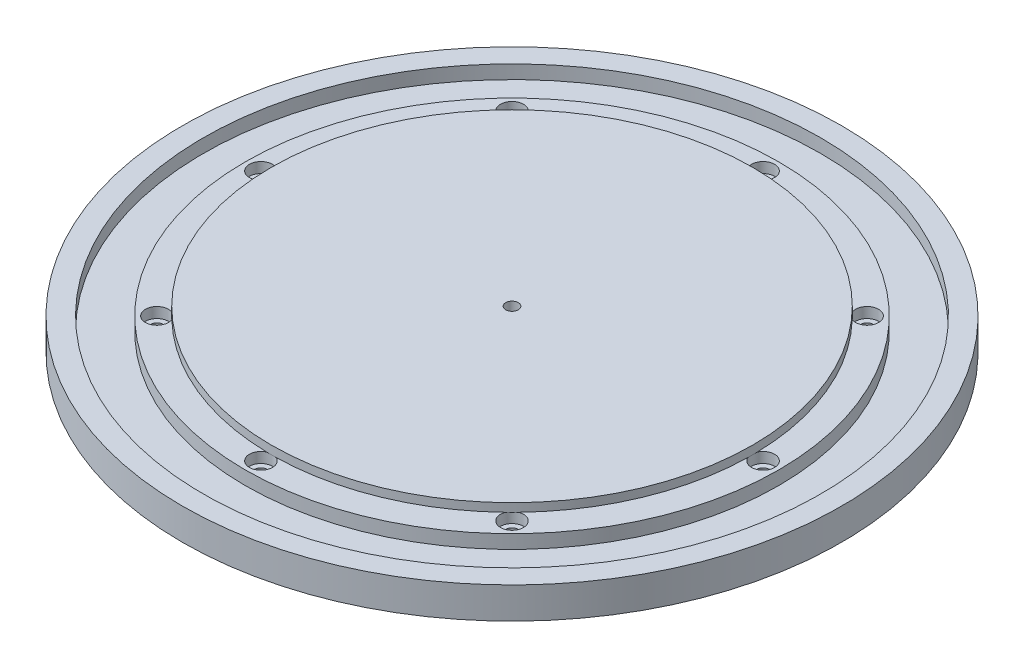
SolidWorks part; units mm, degrees
ref_plane "Front Plane" through (0, 0, 0) normal (0, 0, 1) x (1, 0, 0)
ref_plane "Top Plane" through (0, 0, 0) normal (0, 1, 0) x (1, 0, 0)
ref_plane "Right Plane" through (0, 0, 0) normal (1, 0, 0) x (0, 0, -1)
sketch "Sketch1" plane through (0, 0, 0) normal (1, 0, 0) x (0, 0, -1)
  line L0 (0, -1000) -> (0, 49000) construction
  line L12 (-315, 14.606) -> (-315, 44.606)
  line L13 (-315, 44.606) -> (-295, 44.606)
  line L14 (-295, 44.606) -> (-295, 31.606)
  line L15 (-295, 31.606) -> (-255, 31.606)
  line L16 (-255, 31.606) -> (-255, 44.606)
  line L18 (-255, 44.606) -> (-230, 44.606)
  line L19 (-315, 14.606) -> (-229.5, 14.606)
  line L21 (-229.5, 14.606) -> (0, 14.606)
  line L22 (0, 14.606) -> (0, 44.606)
  line L24 (-230, 44.606) -> (-230, 52.606)
  line L25 (-230, 52.606) -> (0, 52.606)
  line L26 (0, 52.606) -> (0, 44.606)
  dimension "D1" = 30
  dimension "D2" = 13
  dimension "D3" = 8
  dimension "D4" = 630
  dimension "D5" = 460
  dimension "D6" = 40
  dimension "D9" = 20
  dimension "D10" = 510
  dimension "D11" = 13
revolve "Revolve1" add sketch "Sketch1" angle 360 about L0
sketch "Sketch2" plane through (0, 44.606, 0) normal (0, 1, 0) x (1, 0, 0)
  line L0 (0, -1000) -> (0, 49000) construction
  line L1 (-1000, 0) -> (49000, 0) construction
  circle A0 centre (0, 240) radius 11
  circle A1 centre (169.7056, 169.7056) radius 11
  circle A2 centre (240, 0) radius 11
  circle A3 centre (169.7056, -169.7056) radius 11
  circle A4 centre (0, -240) radius 11
  circle A5 centre (-169.7056, -169.7056) radius 11
  circle A6 centre (-240, 0) radius 11
  circle A7 centre (-169.7056, 169.7056) radius 11
  point P23 (0, 0)
  dimension "D1" = 240
  dimension "D2" = 22
  dimension "D3" = 8
extrude "Cut-Extrude1" cut sketch "Sketch2" against normal blind 10
sketch "Sketch3" plane through (0, 44.606, 0) normal (0, 1, 0) x (1, 0, 0)
  line L0 (0, -1000) -> (0, 49000) construction
  line L1 (-1000, 0) -> (49000, 0) construction
  circle A0 centre (0, 240) radius 6
  circle A1 centre (169.7056, 169.7056) radius 6
  circle A2 centre (240, 0) radius 6
  circle A3 centre (169.7056, -169.7056) radius 6
  circle A4 centre (0, -240) radius 6
  circle A5 centre (-169.7056, -169.7056) radius 6
  circle A6 centre (-240, 0) radius 6
  circle A7 centre (-169.7056, 169.7056) radius 6
  point P25 (0, 0)
  dimension "D1" = 240
  dimension "D2" = 12
  dimension "D3" = 8
extrude "Cut-Extrude2" cut sketch "Sketch3" against normal through all
sketch "Sketch4" plane through (0, 14.606, 0) normal (0, 1, 0) x (1, 0, 0)
  circle A0 centre (0, 0) radius 6
  dimension "D1" = 12
extrude "Cut-Extrude3" cut sketch "Sketch4" against normal blind 69 and the other way blind 88
